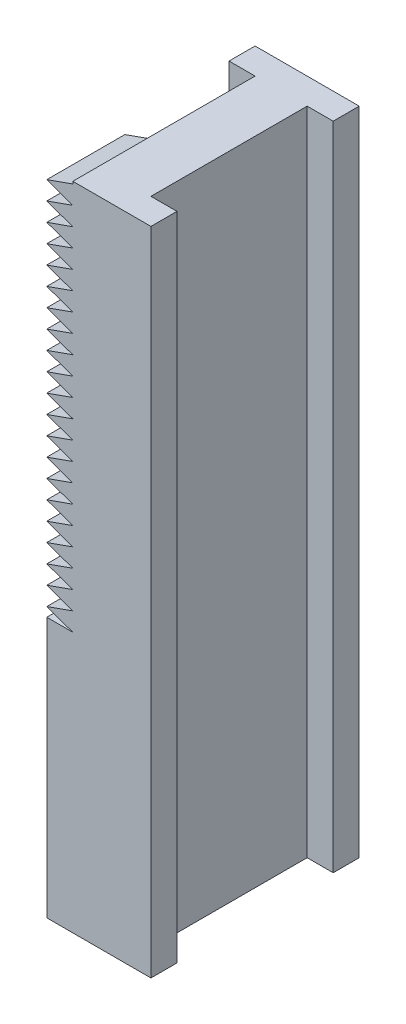
SolidWorks part; units mm, degrees
ref_plane "Front Plane" through (0, 0, 0) normal (0, 0, 1) x (1, 0, 0)
ref_plane "Top Plane" through (0, 0, 0) normal (0, 1, 0) x (1, 0, 0)
ref_plane "Right Plane" through (0, 0, 0) normal (1, 0, 0) x (0, 0, -1)
sketch "Sketch1" plane through (0, 0, 0) normal (0, 1, 0) x (1, 0, 0)
  line L0 (0, 0) -> (0, 4) construction
  line L1 (2, 4) -> (-2, 4)
  line L2 (-2, 4) -> (-2, 3)
  line L3 (-2, 3) -> (-1, 3)
  line L4 (-1, 3) -> (-1, 0)
  line L5 (-1, 0) -> (0, 0) construction
  line L6 (1, 3) -> (1, 0)
  line L7 (2, 3) -> (1, 3)
  line L8 (2, 4) -> (2, 3)
  line L9 (-1, 0) -> (1, 0)
  dimension "D1" = 4
  dimension "D2" = 2
  dimension "D3" = 1
  dimension "D4" = 1
extrude "Boss-Extrude1" add sketch "Sketch1" along normal blind 25
mirror "Mirror1" about plane through (-1, 25, 0) normal (0, 0, -1) of "Boss-Extrude1"
sketch "Sketch2" plane through (0, 25, 0) normal (0, 1, 0) x (1, 0, 0)
  line L1 (-1, -3) -> (-2, -3)
  line L2 (-1, -3) -> (-1, -4)
  line L3 (-1, -4) -> (-2, -4)
  line L4 (-2, -3) -> (-2, -4)
extrude "Cut-Extrude1" cut sketch "Sketch2" against normal blind 15
sketch "Sketch3" plane through (0, 0, 4) normal (0, 0, 1) x (1, 0, 0)
  line L0 (-1, 10) -> (-2, 10.355)
  line L1 (-1, 10) -> (-1, 10.355) construction
  line L2 (-1, 10) -> (-1, 25) construction
  line L3 (-1, 10.355) -> (-2, 10.355) construction
  line L4 (-1, 10.71) -> (-2, 10.355)
  line L5 (-1, 10.71) -> (-1, 10)
  dimension "D1" = 1
  dimension "D2" = 0.355
extrude "Boss-Extrude2" add sketch "Sketch3" against normal blind 3
pattern_linear "LPattern1" count 21 spacing 0.71 along (0, 1, 0) of "Boss-Extrude2"
